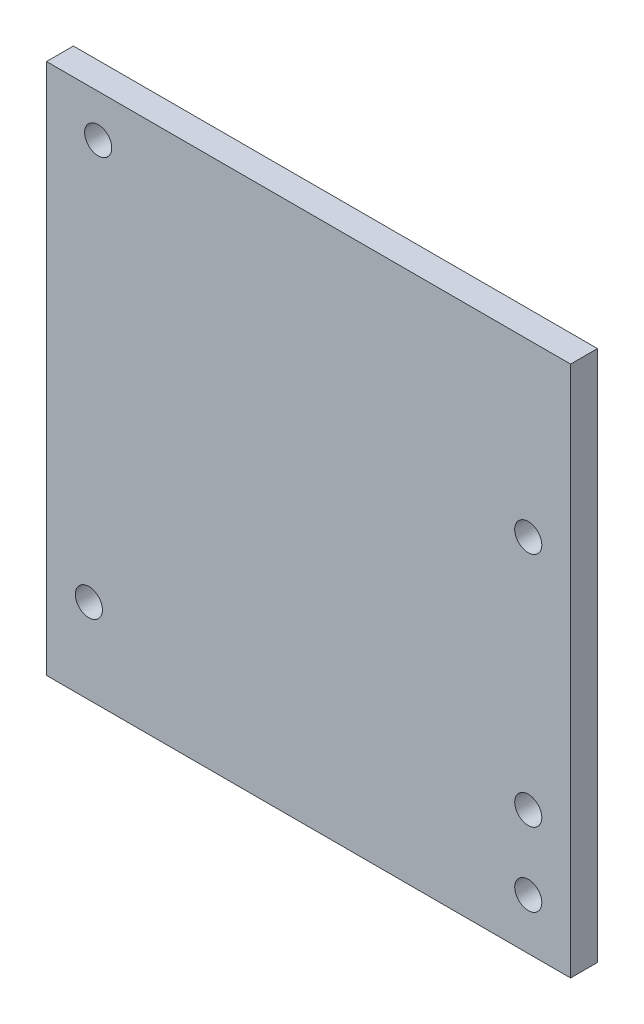
SolidWorks part; units mm, degrees
ref_plane "Front Plane" through (0, 0, 0) normal (0, 0, 1) x (1, 0, 0)
ref_plane "Top Plane" through (0, 0, 0) normal (0, 1, 0) x (1, 0, 0)
ref_plane "Right Plane" through (0, 0, 0) normal (1, 0, 0) x (0, 0, -1)
sketch "Sketch1" plane through (0, 0, 0) normal (0, 0, 1) x (1, 0, 0)
  line L1 (0, 0) -> (61.9, 0)
  line L2 (0, 0) -> (0, 62.8)
  line L3 (0, 62.8) -> (61.9, 62.8)
  line L4 (61.9, 0) -> (61.9, 62.8)
  circle A0 centre (6.1, 57.8) radius 1.6
  circle A1 centre (5, 10) radius 1.6
  circle A2 centre (56.9, 42.6) radius 1.6
  circle A3 centre (56.9, 14.7) radius 1.6
  circle A4 centre (56.9, 6) radius 1.6
  dimension "D1" = 3.2
  dimension "D2" = 3.2
  dimension "D3" = 3.2
  dimension "D4" = 27.9
  dimension "D5" = 15.2
  dimension "D6" = 3.2
  dimension "D7" = 51.9
  dimension "D8" = 4.7
  dimension "D9" = 50.8
  dimension "D14" = 3.2
  dimension "D15" = 36.6
  dimension "D10" = 5
  dimension "D11" = 5
  dimension "D12" = 10
  dimension "D13" = 5
extrude "Boss-Extrude1" add sketch "Sketch1" along normal blind 3.175
